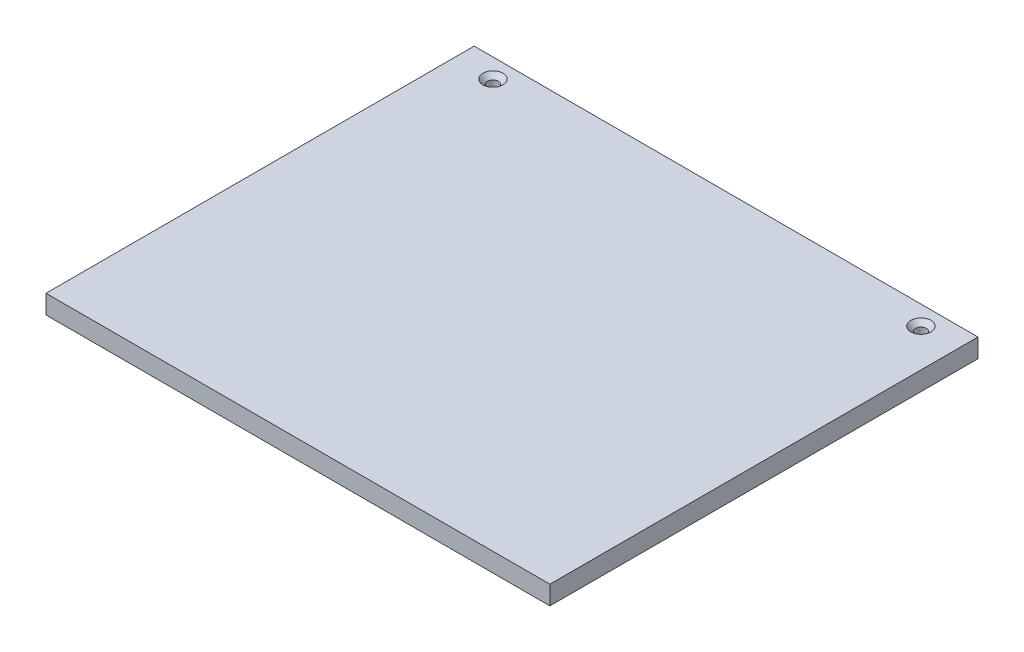
SolidWorks part; units mm, degrees
material "Acrylic (Medium-high impact)"
ref_plane "Front Plane" through (0, 0, 0) normal (0, 0, 1) x (1, 0, 0)
ref_plane "Top Plane" through (0, 0, 0) normal (0, 1, 0) x (1, 0, 0)
ref_plane "Right Plane" through (0, 0, 0) normal (1, 0, 0) x (0, 0, -1)
sketch "Sketch1" plane through (0, 0, 0) normal (0, 1, 0) x (1, 0, 0)
  line L1 (-79, 67.125) -> (79, 67.125)
  line L2 (-79, 67.125) -> (-79, -67.125)
  line L3 (-79, -67.125) -> (79, -67.125)
  line L4 (79, 67.125) -> (79, -67.125)
  line L5 (-79, 67.125) -> (79, -67.125) construction
  line L6 (-79, -67.125) -> (79, 67.125) construction
  point P0 (0, 0)
  dimension "D1" = 158
  dimension "D2" = 134.25
extrude "Boss-Extrude1" add sketch "Sketch1" along normal blind 5.9
hole_wizard "CSK for M3 Flat Head Machine Screw1" positions "Sketch2" profile "Sketch3" countersink size "M3" standard "ANSI Metric"
sketch "Sketch2" plane through (0, 5.9, 0) normal (0, 1, 0) x (1, 0, 0)
  point P0 (-67.1, 61.125)
  point P3 (67.1, 61.125)
sketch "Sketch3" plane through (-67.1, 5.9, -61.125) normal (1, 0, 0) x (0, 0, 1)
  line L0 (0, 0) -> (0, 11.0215)
  line L1 (0, 11.0215) -> (1.7, 10)
  line L2 (1.7, 10) -> (1.7, 1.45)
  line L3 (1.7, 1.45) -> (3.15, 0)
  line L5 (3.15, 0) -> (0, 0)
  line L6 (-1.7, 1.45) -> (-3.15, 0) construction
  line L10 (0, 11.0215) -> (-1.7, 10) construction
  line L11 (0, -6.35) -> (0, 107.95) construction
  dimension "Hole Dia." = 3.4
  dimension "Hole Depth" = 10
  dimension "Near C'Sink Dia." = 6.3
  dimension "Near C'Sink Angle" = 90
  dimension "Drill Angle" = 118
hole_wizard "CSK for #4 Flat Head Machine Screw (100)1" positions "Sketch4" profile "Sketch5" countersink size "#4" standard "ANSI Inch"
sketch "Sketch4" plane through (0, 0, 0) normal (0, -1, 0) x (-1, 0, 0)
  point P0 (65, -51.875)
  point P3 (-65, -51.875)
sketch "Sketch5" plane through (-65, 0, 51.875) normal (1, 0, 0) x (0, 0, -1)
  line L0 (0, 0) -> (0, 10.9806)
  line L1 (0, 10.9806) -> (1.6319, 10)
  line L2 (1.6319, 10) -> (1.6319, 1.0284)
  line L3 (1.6319, 1.0284) -> (2.8575, 0)
  line L5 (2.8575, 0) -> (0, 0)
  line L6 (-1.6319, 1.0284) -> (-2.8575, 0) construction
  line L10 (0, 10.9806) -> (-1.632, 10) construction
  line L11 (0, -6.35) -> (0, 107.95) construction
  dimension "Hole Dia." = 3.2639
  dimension "Hole Depth" = 10
  dimension "Near C'Sink Dia." = 5.715
  dimension "Near C'Sink Angle" = 100
  dimension "Drill Angle" = 118
